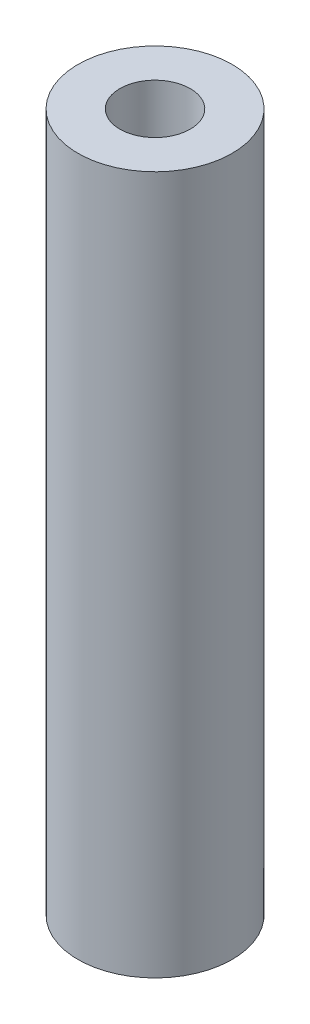
SolidWorks part; units mm, degrees
ref_plane "Front Plane" through (0, 0, 0) normal (0, 0, 1) x (1, 0, 0)
ref_plane "Top Plane" through (0, 0, 0) normal (0, 1, 0) x (1, 0, 0)
ref_plane "Right Plane" through (0, 0, 0) normal (1, 0, 0) x (0, 0, -1)
sketch "Sketch1" plane through (0, 0, 0) normal (0, 0, 1) x (1, 0, 0)
  line L0 (0, 0) -> (0, 63.5) construction
  line L1 (3.2004, 0) -> (7.0104, 0)
  line L2 (3.2004, 0) -> (3.2004, 63.5)
  line L3 (3.2004, 63.5) -> (7.0104, 63.5)
  line L4 (7.0104, 0) -> (7.0104, 63.5)
  line L5 (5.1054, 63.5) -> (5.1054, 0) construction
  line L6 (3.2004, 31.75) -> (7.0104, 31.75) construction
  point P212 (5.1054, 31.75)
  dimension "D1" = 3.2004
  dimension "D2" = 3.81
  dimension "D3" = 63.5
revolve "Revolve1" add sketch "Sketch1" angle 360 about L0
